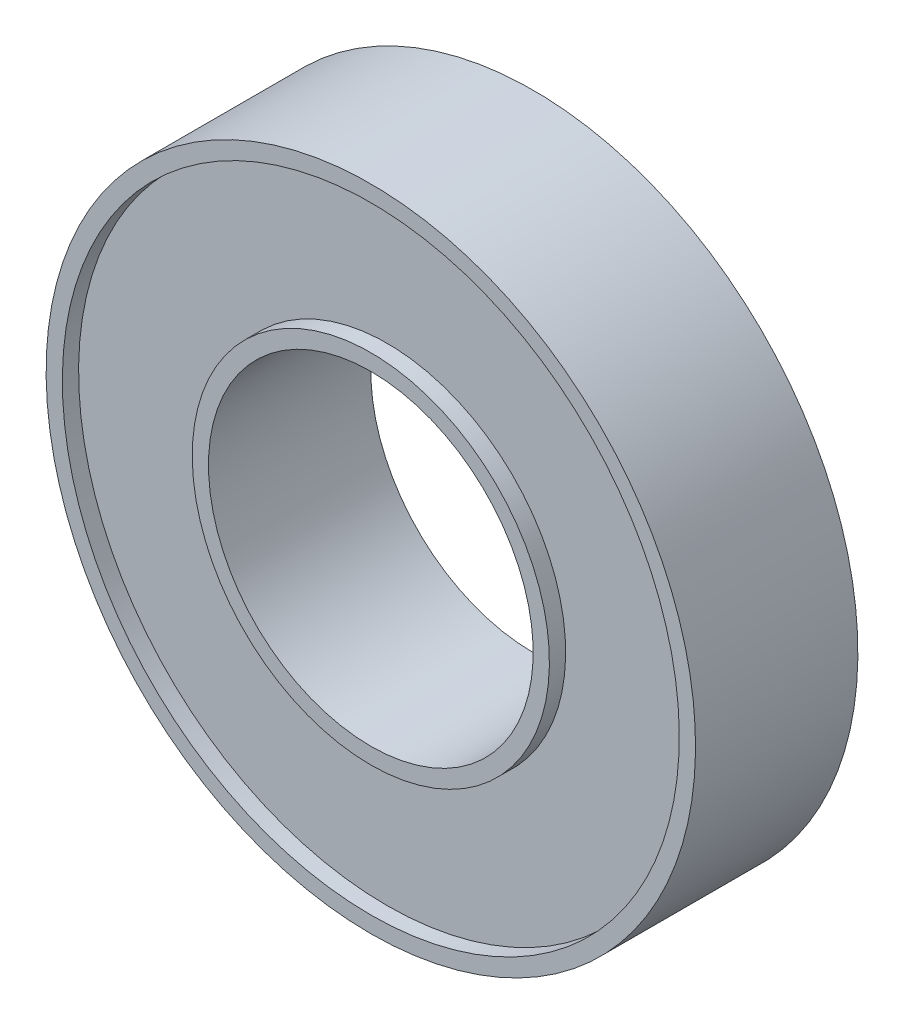
SolidWorks part; units mm, degrees
ref_plane "Front Plane" through (0, 0, 0) normal (0, 0, 1) x (1, 0, 0)
ref_plane "Top Plane" through (0, 0, 0) normal (0, 1, 0) x (1, 0, 0)
ref_plane "Right Plane" through (0, 0, 0) normal (1, 0, 0) x (0, 0, -1)
sketch "Sketch1" plane through (0, 0, 0) normal (1, 0, 0) x (0, 0, -1)
  line L0 (-4, 19) -> (4, 19) construction
  line L1 (-5, 20) -> (5, 20)
  line L2 (-5, 20) -> (-5, 19)
  line L3 (-5, 19) -> (-4, 19)
  line L4 (5, 20) -> (5, 19)
  line L5 (-5, 19) -> (-5, 11) construction
  line L6 (-5, 11) -> (-4, 11)
  line L7 (-4, 19) -> (-4, 11)
  line L8 (5, 19) -> (4, 19)
  line L9 (5, 19) -> (5, 11) construction
  line L10 (-5, 11) -> (-5, 10)
  line L11 (-5, 10) -> (5, 10)
  line L12 (5, 11) -> (5, 10)
  line L13 (5, 11) -> (4, 11)
  line L14 (-5, 10) -> (-5, 0) construction
  line L15 (-5, 0) -> (5, 0) construction
  line L16 (5, 10) -> (5, 0) construction
  line L17 (4, 19) -> (4, 11)
  line L18 (-4, 11) -> (4, 11) construction
  point P2 (0, 0)
  dimension "D1" = 1
  dimension "D2" = 1
  dimension "D3" = 10
  dimension "D4" = 10
  dimension "D5" = 1
  dimension "D6" = 10
revolve "Revolve2" add sketch "Sketch1" angle 360 about L15
